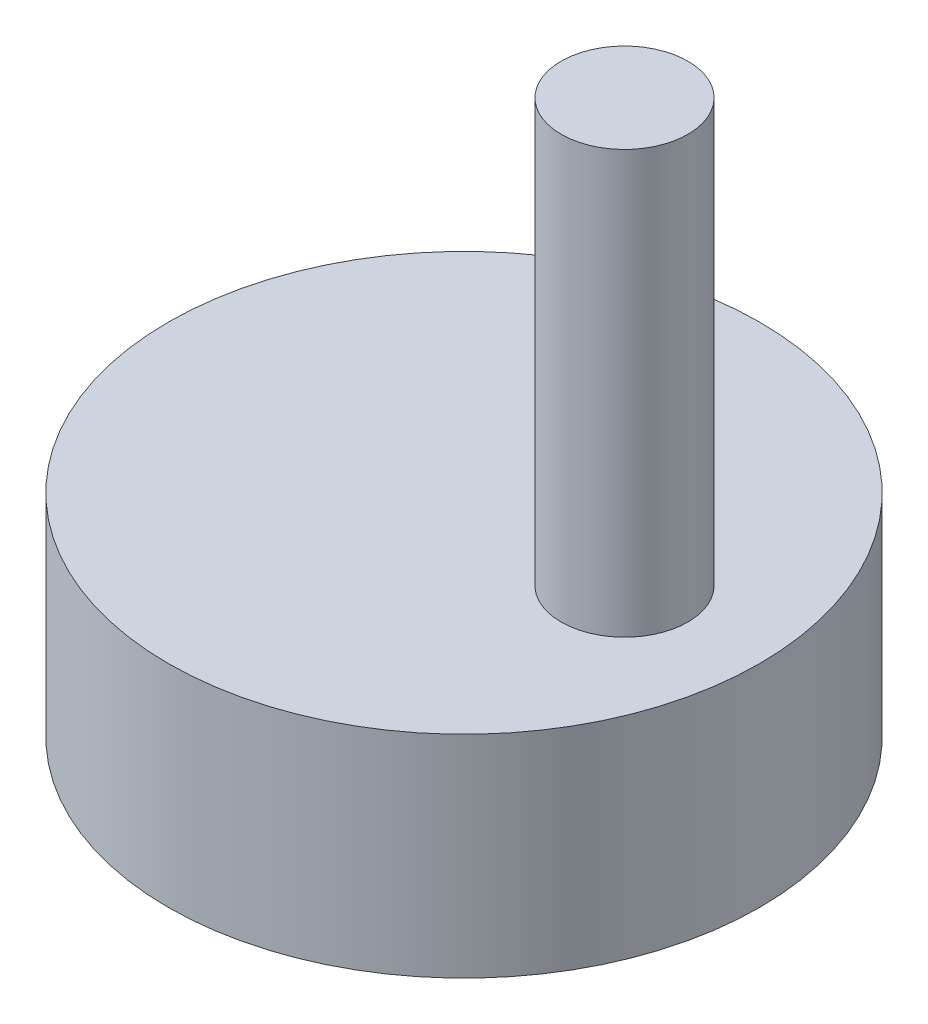
SolidWorks part; units mm, degrees
ref_plane "Front Plane" through (0, 0, 0) normal (0, 0, 1) x (1, 0, 0)
ref_plane "Top Plane" through (0, 0, 0) normal (0, 1, 0) x (1, 0, 0)
ref_plane "Right Plane" through (0, 0, 0) normal (1, 0, 0) x (0, 0, -1)
sketch "Sketch1" plane through (0, 0, 0) normal (0, 1, 0) x (1, 0, 0)
  circle A0 centre (0, 0) radius 70
  dimension "D1" = 140
extrude "Boss-Extrude1" add sketch "Sketch1" along normal blind 50
sketch "Sketch2" plane through (0, 50, 0) normal (0, 1, 0) x (1, 0, 0)
  line L0 (-55, 0) -> (55, 0) construction
  circle A0 centre (38, 0) radius 15
  dimension "D1" = 30
  dimension "D2" = 38
extrude "Boss-Extrude2" add sketch "Sketch2" along normal blind 100
